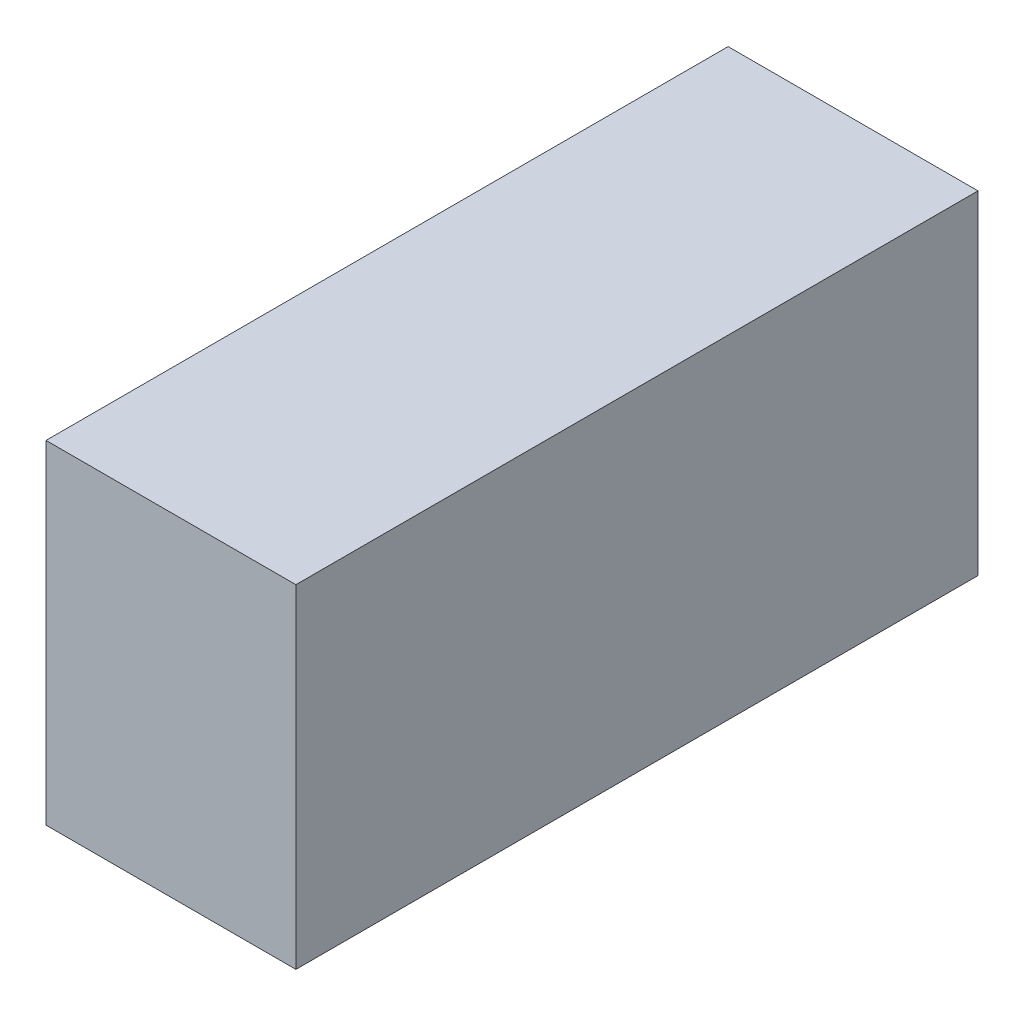
SolidWorks part; units mm, degrees
ref_plane "Front Plane" through (0, 0, 0) normal (0, 0, 1) x (1, 0, 0)
ref_plane "Top Plane" through (0, 0, 0) normal (0, 1, 0) x (1, 0, 0)
ref_plane "Right Plane" through (0, 0, 0) normal (1, 0, 0) x (0, 0, -1)
sketch "Sketch2" plane through (0, 0, 0) normal (0, 0, 1) x (1, 0, 0)
  line L1 (-0.4375, 2.675) -> (-5.2, 2.675)
  line L2 (-0.4375, 2.675) -> (-0.4375, -3.675)
  line L3 (-0.4375, -3.675) -> (-5.2, -3.675)
  line L4 (-5.2, 2.675) -> (-5.2, -3.675)
  dimension "D1" = 4.7625
  dimension "D2" = 6.35
extrude "Boss-Extrude1" add sketch "Sketch2" along normal blind 13
